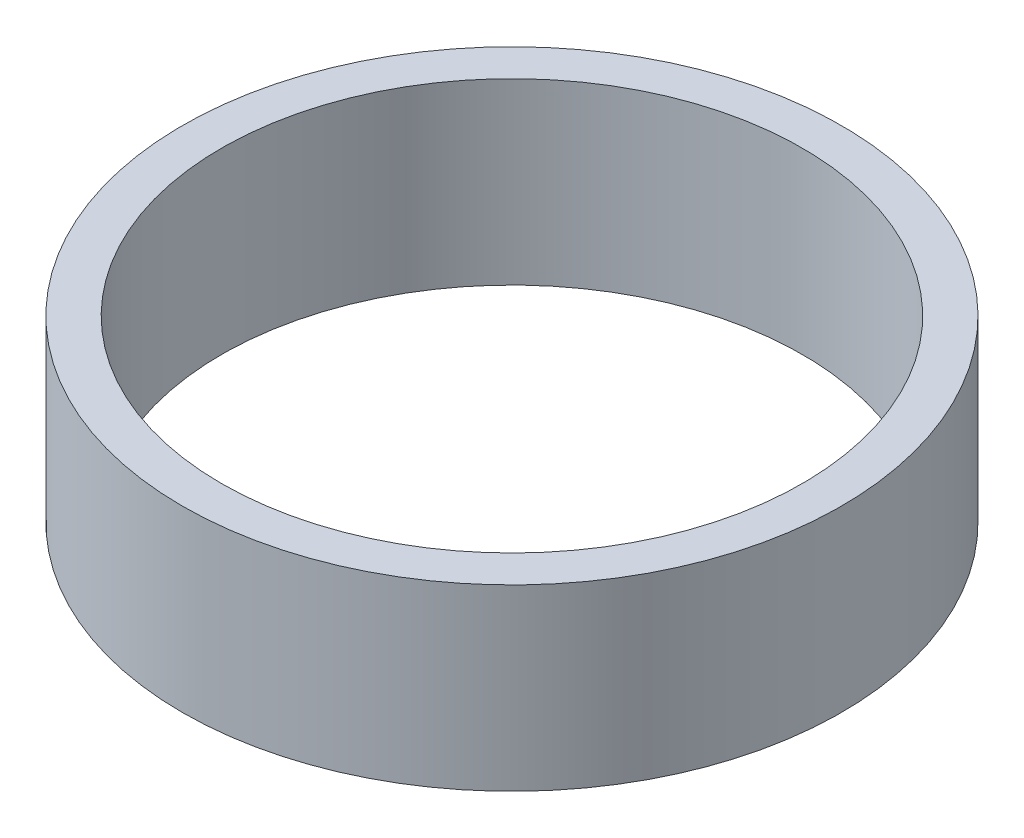
SolidWorks part; units mm, degrees
ref_plane "Front Plane" through (0, 0, 0) normal (0, 0, 1) x (1, 0, 0)
ref_plane "Top Plane" through (0, 0, 0) normal (0, 1, 0) x (1, 0, 0)
ref_plane "Right Plane" through (0, 0, 0) normal (1, 0, 0) x (0, 0, -1)
sketch "Sketch1" plane through (0, 0, 0) normal (0, 1, 0) x (1, 0, 0)
  circle A0 centre (0, 0) radius 13
  circle A1 centre (0, 0) radius 14.75
  dimension "D1" = 29.5
  dimension "D2" = 26
extrude "Boss-Extrude1" add sketch "Sketch1" along normal blind 8
